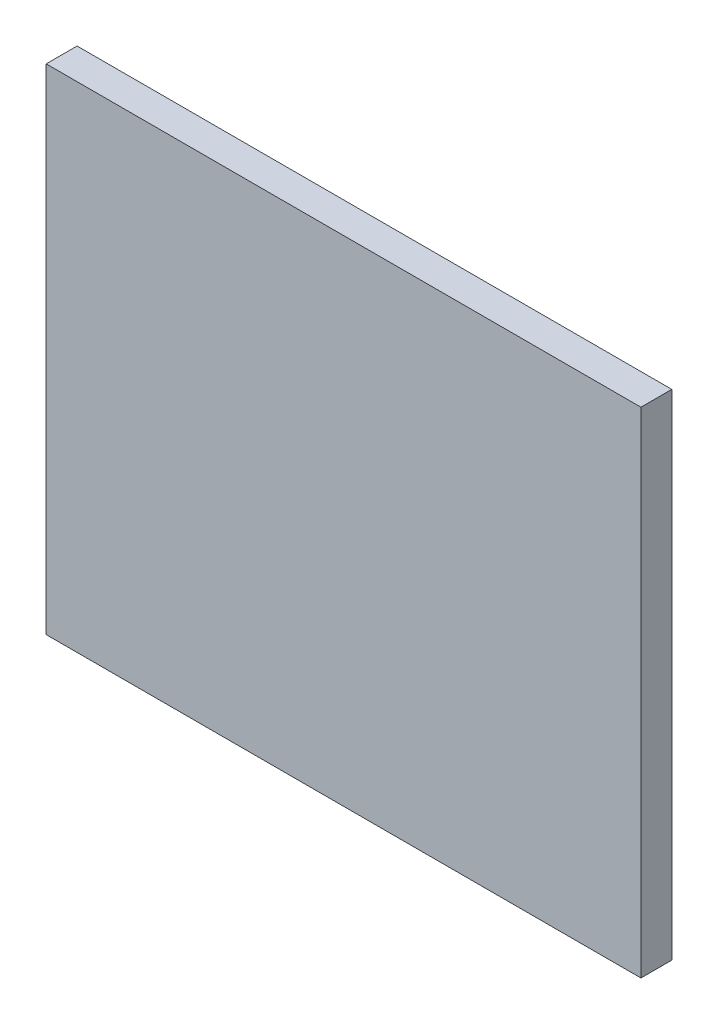
SolidWorks part; units mm, degrees
ref_plane "Front Plane" through (0, 0, 0) normal (0, 0, 1) x (1, 0, 0)
ref_plane "Top Plane" through (0, 0, 0) normal (0, 1, 0) x (1, 0, 0)
ref_plane "Right Plane" through (0, 0, 0) normal (1, 0, 0) x (0, 0, -1)
sketch "Sketch1" plane through (0, 0, 0) normal (0, 0, 1) x (1, 0, 0)
  line L1 (-38.5, -32) -> (38.5, -32)
  line L2 (-38.5, -32) -> (-38.5, 32)
  line L3 (-38.5, 32) -> (38.5, 32)
  line L4 (38.5, -32) -> (38.5, 32)
  line L5 (-38.5, -32) -> (38.5, 32) construction
  line L6 (-38.5, 32) -> (38.5, -32) construction
  point P0 (0, 0)
  dimension "D1" = 77
  dimension "D2" = 64
extrude "Boss-Extrude1" add sketch "Sketch1" along normal blind 4
sketch "Sketch3" plane through (0, 0, 4) normal (0, 0, 1) x (1, 0, 0)
  line L0 (38.5, 32) -> (-38.5, 32) construction
  line L1 (-35, 28.88) -> (35, 28.88)
  line L2 (-35, 28.88) -> (-35, -23.62)
  line L3 (-35, -23.62) -> (35, -23.62)
  line L4 (35, 28.88) -> (35, -23.62)
  line L6 (38.5, 32) -> (-38.5, 32) construction
  point P6 (0, 32)
  dimension "D1" = 70
  dimension "D2" = 52.5
  dimension "D3" = 3.12
  dimension "D4" = 35
